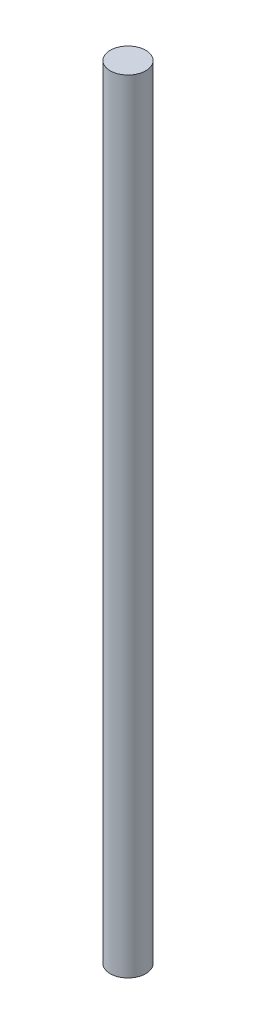
SolidWorks part; units mm, degrees
ref_plane "Front Plane" through (0, 0, 0) normal (0, 0, 1) x (1, 0, 0)
ref_plane "Top Plane" through (0, 0, 0) normal (0, 1, 0) x (1, 0, 0)
ref_plane "Right Plane" through (0, 0, 0) normal (1, 0, 0) x (0, 0, -1)
sketch "Sketch1" plane through (0, 0, 0) normal (0, 1, 0) x (1, 0, 0)
  circle A0 centre (0, 0) radius 0.5
extrude "Boss-Extrude1" add sketch "Sketch1" along normal blind 22
